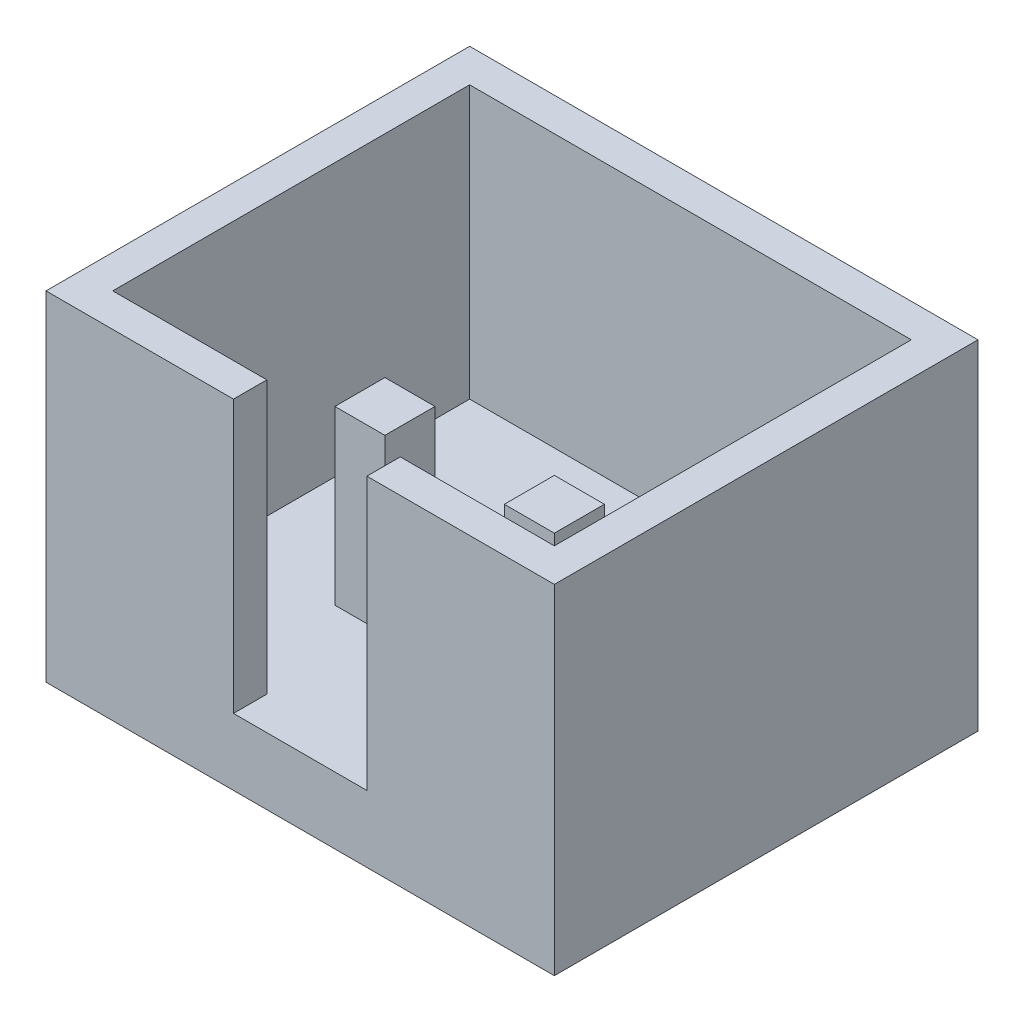
SolidWorks part; units mm, degrees
ref_plane "前视基准面" through (0, 0, 0) normal (0, 0, 1) x (1, 0, 0)
ref_plane "上视基准面" through (0, 0, 0) normal (0, 1, 0) x (1, 0, 0)
ref_plane "右视基准面" through (0, 0, 0) normal (1, 0, 0) x (0, 0, -1)
sketch "草图1" plane through (0, 0, 0) normal (0, 1, 0) x (1, 0, 0)
  line L0 (0, 7.1914) -> (0, -5.4429) construction
  line L1 (-3.81, 3.175) -> (3.81, 3.175)
  line L2 (-3.81, 3.175) -> (-3.81, -3.175)
  line L3 (-3.81, -3.175) -> (3.81, -3.175)
  line L4 (3.81, 3.175) -> (3.81, -3.175)
  line L5 (-10.6234, 0) -> (16.1963, 0) construction
  dimension "D1" = 7.62
  dimension "D2" = 6.35
extrude "拉伸1" add sketch "草图1" along normal blind 5.08
sketch "草图2" plane through (0, 5.08, 0) normal (0, 1, 0) x (-1, 0, 0)
  line L8 (3.31, -2.675) -> (3.31, 2.675)
  line L9 (3.31, 2.675) -> (-3.31, 2.675)
  line L10 (-3.31, 2.675) -> (-3.31, -2.675)
  line L11 (-3.31, -2.675) -> (3.31, -2.675)
  line L12 (3.31, -2.675) -> (3.31, 2.675)
  line L13 (3.31, 2.675) -> (-3.31, 2.675)
  line L14 (-3.31, 2.675) -> (-3.31, -2.675)
  line L15 (-3.31, -2.675) -> (3.31, -2.675)
  dimension "D1" = 0.5
extrude "切除-拉伸1" cut sketch "草图2" against normal offset from surface (4.08 mm away) 1 up to face at (0, 0, 0)
sketch "草图3" plane through (0, 0, 3.175) normal (0, 0, 1) x (1, 0, 0)
  line L0 (-3.81, 5.08) -> (3.81, 5.08) construction
  line L1 (-1, 5.08) -> (1, 5.08)
  line L2 (-1, 5.08) -> (-1, 1)
  line L3 (-1, 1) -> (1, 1)
  line L4 (1, 5.08) -> (1, 1)
  line L5 (3.31, 1) -> (-3.31, 1) construction
  line L6 (0, -1.5083) -> (0, 12.2426) construction
  dimension "D1" = 2
extrude "切除-拉伸2" cut sketch "草图3" against normal blind 1
sketch "草图4" plane through (0, 0, 0) normal (0, -1, 0) x (1, 0, 0)
  line L0 (7.6775, 0.635) -> (-8.5467, 0.635) construction
  line L2 (0, -3.6953) -> (0, 4.0669) construction
  line L3 (-1.27, 2.1009) -> (-1.27, -0.7012) construction
  line L4 (-1.645, 1.01) -> (-0.895, 1.01)
  line L5 (-1.645, 1.01) -> (-1.645, 0.26)
  line L6 (-1.645, 0.26) -> (-0.895, 0.26)
  line L7 (-0.895, 1.01) -> (-0.895, 0.26)
  line L8 (0.895, 1.01) -> (1.645, 1.01)
  line L9 (0.895, 1.01) -> (0.895, 0.26)
  line L10 (0.895, 0.26) -> (1.645, 0.26)
  line L11 (1.645, 1.01) -> (1.645, 0.26)
  dimension "D2" = 0.75
  dimension "D3" = 0.75
  dimension "D4" = 1.27
extrude "拉伸2" add sketch "草图4" along normal blind 2 and the other way offset from surface (3.58 mm away) 1.5 other way up to face at (0, 5.08, 0.975)
